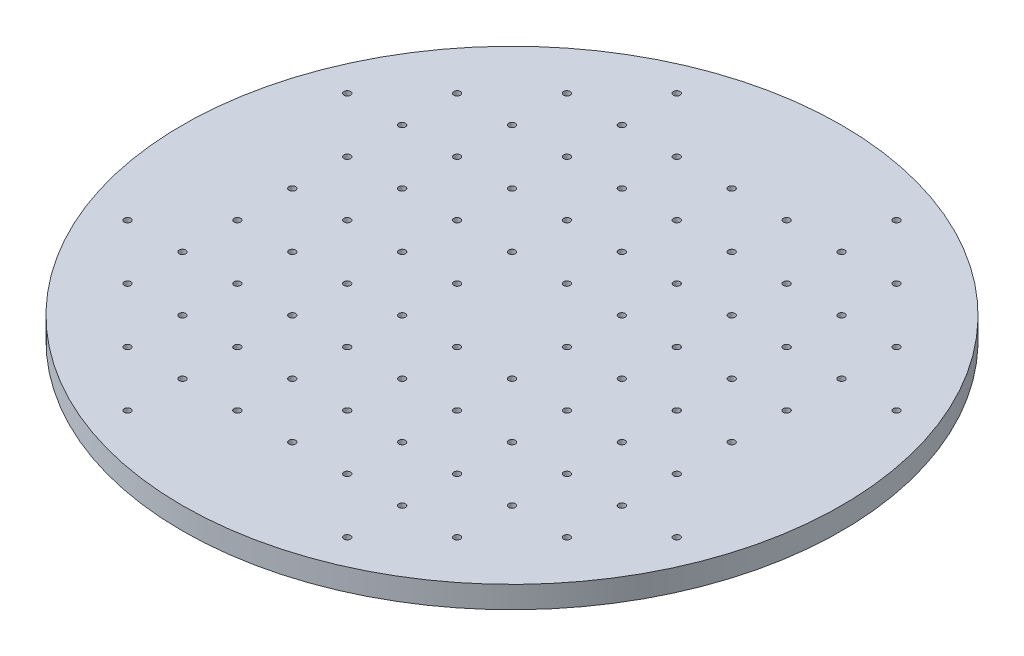
SolidWorks part; units mm, degrees
ref_plane "Спереди" through (0, 0, 0) normal (0, 0, 1) x (1, 0, 0)
ref_plane "Сверху" through (0, 0, 0) normal (0, 1, 0) x (1, 0, 0)
ref_plane "Справа" through (0, 0, 0) normal (1, 0, 0) x (0, 0, -1)
sketch "Эскиз1" plane through (0, 0, 0) normal (0, 1, 0) x (1, 0, 0)
  line L0 (0, 0) -> (0, 50000) construction
  line L1 (0, 0) -> (50000, 0) construction
  line L2 (-50, 400.4706) -> (-50, -49599.5294) construction
  line L3 (-100, 403.4515) -> (-100, -49596.5485) construction
  line L4 (-150, 406.4323) -> (-150, -49593.5677) construction
  line L5 (-200, 452.6356) -> (-200, -49547.3644) construction
  line L6 (-250, 516.724) -> (-250, -49483.276) construction
  line L7 (-296.586, 50) -> (49703.414, 50) construction
  line L8 (-284.8423, 100) -> (49715.1577, 100) construction
  line L9 (816.7595, 150) -> (-49183.2405, 150) construction
  line L10 (897.3988, 200) -> (-49102.6012, 200) construction
  line L11 (680.0233, 250) -> (-49319.9767, 250) construction
  circle A0 centre (0, 0) radius 300
  circle A1 centre (-50, 50) radius 3
  circle A2 centre (-100, 50) radius 3
  circle A3 centre (-150, 50) radius 3
  circle A4 centre (-200, 50) radius 3
  circle A5 centre (-50, 100) radius 3
  circle A6 centre (-100, 100) radius 3
  circle A7 centre (-150, 100) radius 3
  circle A8 centre (-200, 100) radius 3
  circle A9 centre (-250, 100) radius 3
  circle A10 centre (-50, 150) radius 3
  circle A11 centre (-100, 150) radius 3
  circle A12 centre (-150, 150) radius 3
  circle A13 centre (-200, 150) radius 3
  circle A14 centre (-50, 200) radius 3
  circle A15 centre (-100, 200) radius 3
  circle A16 centre (-150, 200) radius 3
  circle A17 centre (-100, 250) radius 3
  circle A18 centre (-50, 0) radius 3
  circle A19 centre (-150, 0) radius 3
  circle A20 centre (-100, 0) radius 3
  circle A21 centre (-200, 0) radius 3
  circle A22 centre (0, 50) radius 3
  circle A23 centre (0, 100) radius 3
  circle A24 centre (0, 150) radius 3
  circle A25 centre (0, 200) radius 3
  circle A26 centre (200, 0) radius 3
  circle A27 centre (100, 0) radius 3
  circle A28 centre (150, 0) radius 3
  circle A29 centre (50, 0) radius 3
  circle A30 centre (100, 250) radius 3
  circle A31 centre (150, 200) radius 3
  circle A32 centre (100, 200) radius 3
  circle A33 centre (50, 200) radius 3
  circle A34 centre (200, 150) radius 3
  circle A35 centre (150, 150) radius 3
  circle A36 centre (100, 150) radius 3
  circle A37 centre (50, 150) radius 3
  circle A38 centre (250, 100) radius 3
  circle A39 centre (200, 100) radius 3
  circle A40 centre (150, 100) radius 3
  circle A41 centre (100, 100) radius 3
  circle A42 centre (50, 100) radius 3
  circle A43 centre (200, 50) radius 3
  circle A44 centre (150, 50) radius 3
  circle A45 centre (100, 50) radius 3
  circle A46 centre (50, 50) radius 3
  circle A47 centre (50, -50) radius 3
  circle A48 centre (100, -50) radius 3
  circle A49 centre (150, -50) radius 3
  circle A50 centre (200, -50) radius 3
  circle A51 centre (50, -100) radius 3
  circle A52 centre (100, -100) radius 3
  circle A53 centre (150, -100) radius 3
  circle A54 centre (200, -100) radius 3
  circle A55 centre (250, -100) radius 3
  circle A56 centre (50, -150) radius 3
  circle A57 centre (100, -150) radius 3
  circle A58 centre (150, -150) radius 3
  circle A59 centre (200, -150) radius 3
  circle A60 centre (50, -200) radius 3
  circle A61 centre (100, -200) radius 3
  circle A62 centre (150, -200) radius 3
  circle A63 centre (100, -250) radius 3
  circle A64 centre (0, -200) radius 3
  circle A65 centre (0, -150) radius 3
  circle A66 centre (0, -100) radius 3
  circle A67 centre (0, -50) radius 3
  circle A68 centre (-100, -250) radius 3
  circle A69 centre (-150, -200) radius 3
  circle A70 centre (-100, -200) radius 3
  circle A71 centre (-50, -200) radius 3
  circle A72 centre (-200, -150) radius 3
  circle A73 centre (-150, -150) radius 3
  circle A74 centre (-100, -150) radius 3
  circle A75 centre (-50, -150) radius 3
  circle A76 centre (-250, -100) radius 3
  circle A77 centre (-200, -100) radius 3
  circle A78 centre (-150, -100) radius 3
  circle A79 centre (-100, -100) radius 3
  circle A80 centre (-50, -100) radius 3
  circle A81 centre (-200, -50) radius 3
  circle A82 centre (-150, -50) radius 3
  circle A83 centre (-100, -50) radius 3
  circle A84 centre (-50, -50) radius 3
  dimension "D1" = 600
  dimension "D12" = 6
  dimension "D2" = 50
  dimension "D3" = 100
  dimension "D4" = 150
  dimension "D5" = 200
  dimension "D6" = 250
  dimension "D7" = 50
  dimension "D8" = 100
  dimension "D9" = 150
  dimension "D10" = 200
  dimension "D11" = 250
sketch "Эскиз2" plane through (0, 0, 0) normal (0, 1, 0) x (1, 0, 0)
  line L0 (0, 0) -> (0, 50000) construction
  line L1 (0, 0) -> (50000, 0) construction
  line L2 (-50, 400.4706) -> (-50, -49599.5294) construction
  line L3 (-100, 403.4515) -> (-100, -49596.5485) construction
  line L4 (-150, 406.4323) -> (-150, -49593.5677) construction
  line L5 (-200, 452.6356) -> (-200, -49547.3644) construction
  line L6 (-250, 516.724) -> (-250, -49483.276) construction
  line L7 (-296.586, 50) -> (49703.414, 50) construction
  line L8 (-284.8423, 100) -> (49715.1577, 100) construction
  line L9 (816.7595, 150) -> (-49183.2405, 150) construction
  line L10 (897.3988, 200) -> (-49102.6012, 200) construction
  line L11 (680.0233, 250) -> (-49319.9767, 250) construction
  circle A0 centre (0, 0) radius 300
  circle A1 centre (-50, 50) radius 3
  circle A2 centre (-100, 50) radius 3
  circle A3 centre (-150, 50) radius 3
  circle A4 centre (-200, 50) radius 3
  circle A5 centre (-50, 100) radius 3
  circle A6 centre (-100, 100) radius 3
  circle A7 centre (-150, 100) radius 3
  circle A8 centre (-200, 100) radius 3
  circle A9 centre (-250, 100) radius 3
  circle A10 centre (-50, 150) radius 3
  circle A11 centre (-100, 150) radius 3
  circle A12 centre (-150, 150) radius 3
  circle A13 centre (-200, 150) radius 3
  circle A14 centre (-50, 200) radius 3
  circle A15 centre (-100, 200) radius 3
  circle A16 centre (-150, 200) radius 3
  circle A17 centre (-100, 250) radius 3
  circle A18 centre (-50, 0) radius 3
  circle A19 centre (-150, 0) radius 3
  circle A20 centre (-100, 0) radius 3
  circle A21 centre (-200, 0) radius 3
  circle A22 centre (0, 50) radius 3
  circle A23 centre (0, 100) radius 3
  circle A24 centre (0, 150) radius 3
  circle A25 centre (0, 200) radius 3
  circle A26 centre (200, 0) radius 3
  circle A27 centre (100, 0) radius 3
  circle A28 centre (150, 0) radius 3
  circle A29 centre (50, 0) radius 3
  circle A30 centre (100, 250) radius 3
  circle A31 centre (150, 200) radius 3
  circle A32 centre (100, 200) radius 3
  circle A33 centre (50, 200) radius 3
  circle A34 centre (200, 150) radius 3
  circle A35 centre (150, 150) radius 3
  circle A36 centre (100, 150) radius 3
  circle A37 centre (50, 150) radius 3
  circle A38 centre (250, 100) radius 3
  circle A39 centre (200, 100) radius 3
  circle A40 centre (150, 100) radius 3
  circle A41 centre (100, 100) radius 3
  circle A42 centre (50, 100) radius 3
  circle A43 centre (200, 50) radius 3
  circle A44 centre (150, 50) radius 3
  circle A45 centre (100, 50) radius 3
  circle A46 centre (50, 50) radius 3
  circle A47 centre (50, -50) radius 3
  circle A48 centre (100, -50) radius 3
  circle A49 centre (150, -50) radius 3
  circle A50 centre (200, -50) radius 3
  circle A51 centre (50, -100) radius 3
  circle A52 centre (100, -100) radius 3
  circle A53 centre (150, -100) radius 3
  circle A54 centre (200, -100) radius 3
  circle A55 centre (250, -100) radius 3
  circle A56 centre (50, -150) radius 3
  circle A57 centre (100, -150) radius 3
  circle A58 centre (150, -150) radius 3
  circle A59 centre (200, -150) radius 3
  circle A60 centre (50, -200) radius 3
  circle A61 centre (100, -200) radius 3
  circle A62 centre (150, -200) radius 3
  circle A63 centre (100, -250) radius 3
  circle A64 centre (0, -200) radius 3
  circle A65 centre (0, -150) radius 3
  circle A66 centre (0, -100) radius 3
  circle A67 centre (0, -50) radius 3
  circle A68 centre (-100, -250) radius 3
  circle A69 centre (-150, -200) radius 3
  circle A70 centre (-100, -200) radius 3
  circle A71 centre (-50, -200) radius 3
  circle A72 centre (-200, -150) radius 3
  circle A73 centre (-150, -150) radius 3
  circle A74 centre (-100, -150) radius 3
  circle A75 centre (-50, -150) radius 3
  circle A76 centre (-250, -100) radius 3
  circle A77 centre (-200, -100) radius 3
  circle A78 centre (-150, -100) radius 3
  circle A79 centre (-100, -100) radius 3
  circle A80 centre (-50, -100) radius 3
  circle A81 centre (-200, -50) radius 3
  circle A82 centre (-150, -50) radius 3
  circle A83 centre (-100, -50) radius 3
  circle A84 centre (-50, -50) radius 3
  dimension "D1" = 600
  dimension "D12" = 6
  dimension "D2" = 50
  dimension "D3" = 100
  dimension "D4" = 150
  dimension "D5" = 200
  dimension "D6" = 250
  dimension "D7" = 50
  dimension "D8" = 100
  dimension "D9" = 150
  dimension "D10" = 200
  dimension "D11" = 250
extrude "Бобышка-Вытянуть1" add sketch "Эскиз2" along normal blind 20
